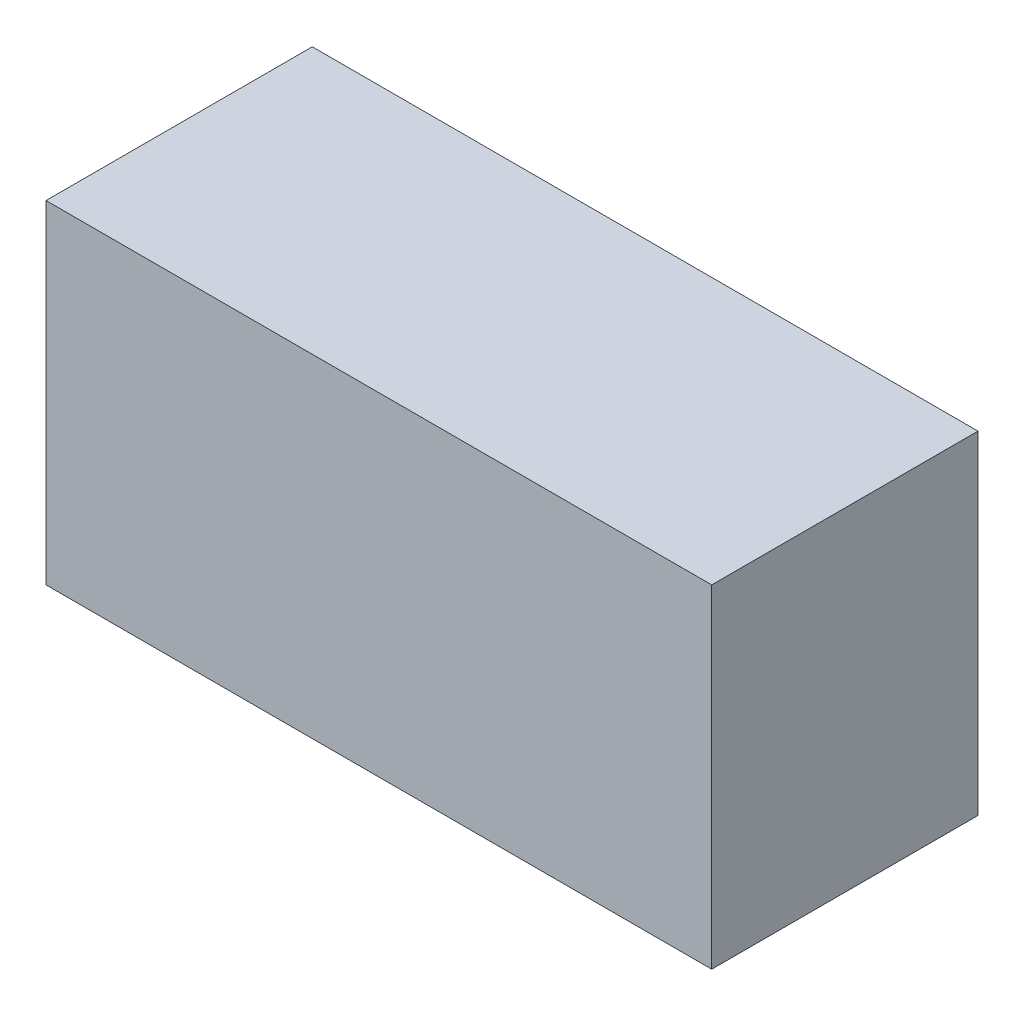
SolidWorks part; units mm, degrees
ref_plane "Front Plane" through (0, 0, 0) normal (0, 0, 1) x (1, 0, 0)
ref_plane "Top Plane" through (0, 0, 0) normal (0, 1, 0) x (1, 0, 0)
ref_plane "Right Plane" through (0, 0, 0) normal (1, 0, 0) x (0, 0, -1)
sketch "Sketch1" plane through (0, 0, 0) normal (0, 0, 1) x (1, 0, 0)
  line L0 (-50, 0) -> (-50, 50)
  line L1 (-50, 50) -> (50, 50)
  line L2 (50, 50) -> (50, 0)
  line L3 (50, 0) -> (-50, 0)
  dimension "D1" = 50
  dimension "D2" = 50
  dimension "D3" = 50
extrude "Boss-Extrude1" add sketch "Sketch1" against normal blind 40
sketch "Sketch2" plane through (0, 0, 0) normal (0, 0, 1) x (1, 0, 0)
  line L1 (-50, 50) -> (-50, 0) construction
  circle A0 centre (0, 25) radius 10
  point P2 (0, 0)
  point P5 (-28.7583, 40.2473)
  dimension "D1" = 20
  dimension "D2" = 25
  dimension "D3" = 50
